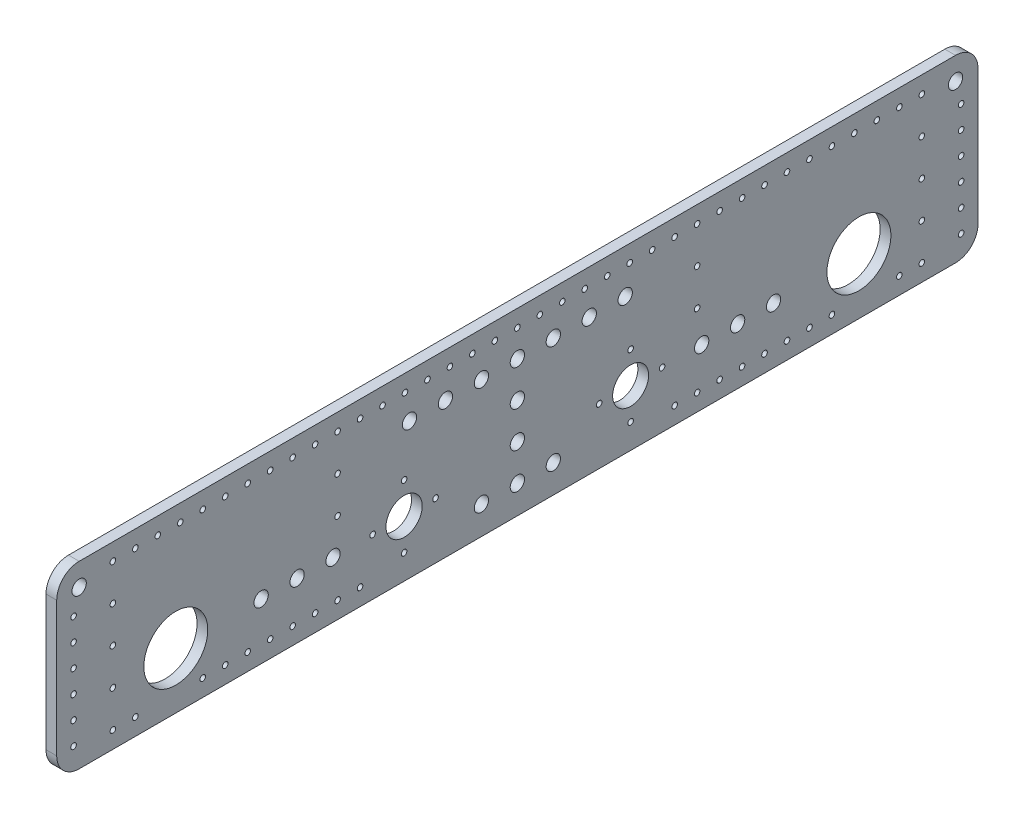
SolidWorks part; units mm, degrees
ref_plane "Front Plane" through (0, 0, 0) normal (0, 0, 1) x (1, 0, 0)
ref_plane "Top Plane" through (0, 0, 0) normal (0, 1, 0) x (1, 0, 0)
ref_plane "Right Plane" through (0, 0, 0) normal (1, 0, 0) x (0, 0, -1)
sketch "Sketch2" plane through (0, 0, 0) normal (1, 0, 0) x (0, 0, -1)
  line L0 (-23.4723, 28.6683) -> (-23.4723, -31.3317)
  line L1 (-13.4723, 38.6683) -> (376.5277, 38.6683)
  line L2 (-13.4723, -41.3317) -> (376.5277, -41.3317)
  line L3 (386.5277, 28.6683) -> (386.5277, -31.3317)
  circle A1 centre (29.5277, -16.3317) radius 14.225
  circle A2 centre (333.5277, -16.3317) radius 14.225
  arc A15 (-23.4723, 28.6683) -> (-13.4723, 38.6683) centre (-13.4723, 28.6683) cw
  arc A16 (-13.4723, -41.3317) -> (-23.4723, -31.3317) centre (-13.4723, -31.3317) cw
  arc A17 (386.5277, 28.6683) -> (376.5277, 38.6683) centre (376.5277, 28.6683) ccw
  arc A18 (376.5277, -41.3317) -> (386.5277, -31.3317) centre (376.5277, -31.3317) ccw
  circle A59 centre (181.5277, -28.7717) radius 3.18
  circle A60 centre (197.5277, -28.7717) radius 3.18
  circle A63 centre (197.5277, 19.2283) radius 3.18
  circle A64 centre (181.5277, -12.7717) radius 3.18
  circle A65 centre (181.5277, 3.2283) radius 3.18
  circle A66 centre (181.5277, 19.2283) radius 3.18
  circle A67 centre (165.5277, -28.7717) radius 3.18
  circle A68 centre (165.5277, 19.2283) radius 3.18
  circle A69 centre (197.5277, -12.7717) radius 3.18 [skipped]
  circle A70 centre (197.5277, 3.2283) radius 3.18 [skipped]
  circle A71 centre (-8.4723, 31.1683) radius 1.25 construction
  circle A150 centre (83.5027, -16.3317) radius 3.18
  circle A151 centre (279.5527, -16.3317) radius 3.18
  circle A152 centre (1.5277, 31.1683) radius 1.25
  circle A153 centre (11.5277, 31.1683) radius 1.25
  circle A154 centre (21.5277, 31.1683) radius 1.25
  circle A155 centre (31.5277, 31.1683) radius 1.25
  circle A156 centre (41.5277, 31.1683) radius 1.25
  circle A157 centre (51.5277, 31.1683) radius 1.25
  circle A158 centre (61.5277, 31.1683) radius 1.25
  circle A159 centre (71.5277, 31.1683) radius 1.25
  circle A160 centre (81.5277, 31.1683) radius 1.25
  circle A161 centre (91.5277, 31.1683) radius 1.25
  circle A162 centre (101.5277, 31.1683) radius 1.25
  circle A163 centre (111.5277, 31.1683) radius 1.25
  circle A164 centre (121.5277, 31.1683) radius 1.25
  circle A165 centre (131.5277, 31.1683) radius 1.25
  circle A166 centre (141.5277, 31.1683) radius 1.25
  circle A167 centre (151.5277, 31.1683) radius 1.25
  circle A168 centre (161.5277, 31.1683) radius 1.25
  circle A169 centre (171.5277, 31.1683) radius 1.25
  circle A170 centre (181.5277, 31.1683) radius 1.25
  circle A171 centre (191.5277, 31.1683) radius 1.25
  circle A172 centre (201.5277, 31.1683) radius 1.25
  circle A173 centre (211.5277, 31.1683) radius 1.25
  circle A174 centre (221.5277, 31.1683) radius 1.25
  circle A175 centre (231.5277, 31.1683) radius 1.25
  circle A176 centre (241.5277, 31.1683) radius 1.25
  circle A177 centre (251.5277, 31.1683) radius 1.25
  circle A178 centre (261.5277, 31.1683) radius 1.25
  circle A179 centre (271.5277, 31.1683) radius 1.25
  circle A180 centre (281.5277, 31.1683) radius 1.25
  circle A181 centre (291.5277, 31.1683) radius 1.25
  circle A182 centre (301.5277, 31.1683) radius 1.25
  circle A183 centre (311.5277, 31.1683) radius 1.25
  circle A184 centre (321.5277, 31.1683) radius 1.25
  circle A185 centre (331.5277, 31.1683) radius 1.25
  circle A186 centre (341.5277, 31.1683) radius 1.25
  circle A187 centre (351.5277, 31.1683) radius 1.25
  circle A188 centre (361.5277, 31.1683) radius 1.25
  circle A190 centre (1.5277, -33.8317) radius 1.25
  circle A191 centre (11.5277, -33.8317) radius 1.25
  circle A194 centre (41.5277, -33.8317) radius 1.25
  circle A195 centre (51.5277, -33.8317) radius 1.25
  circle A196 centre (61.5277, -33.8317) radius 1.25
  circle A197 centre (71.5277, -33.8317) radius 1.25
  circle A198 centre (81.5277, -33.8317) radius 1.25
  circle A199 centre (91.5277, -33.8317) radius 1.25
  circle A200 centre (101.5277, -33.8317) radius 1.25
  circle A201 centre (111.5277, -33.8317) radius 1.25
  circle A215 centre (251.5277, -33.8317) radius 1.25
  circle A216 centre (261.5277, -33.8317) radius 1.25
  circle A217 centre (271.5277, -33.8317) radius 1.25
  circle A218 centre (281.5277, -33.8317) radius 1.25
  circle A219 centre (291.5277, -33.8317) radius 1.25
  circle A220 centre (301.5277, -33.8317) radius 1.25
  circle A221 centre (311.5277, -33.8317) radius 1.25
  circle A222 centre (321.5277, -33.8317) radius 1.25
  circle A225 centre (351.5277, -33.8317) radius 1.25
  circle A226 centre (361.5277, -33.8317) radius 1.25
  circle A229 centre (181.5277, -33.8317) radius 1.25 [skipped]
  circle A230 centre (201.5277, -33.8317) radius 1.25 [skipped]
  circle A231 centre (161.5277, -33.8317) radius 1.25 [skipped]
  circle A232 centre (151.5277, -33.8317) radius 1.25 [skipped]
  circle A233 centre (141.5277, -33.8317) radius 1.25 [skipped]
  circle A234 centre (131.5277, -33.8317) radius 1.25 [skipped]
  circle A235 centre (171.5277, -33.8317) radius 1.25 [skipped]
  circle A236 centre (191.5277, -33.8317) radius 1.25 [skipped]
  circle A237 centre (211.5277, -33.8317) radius 1.25 [skipped]
  circle A238 centre (221.5277, -33.8317) radius 1.25 [skipped]
  circle A239 centre (231.5277, -33.8317) radius 1.25 [skipped]
  circle A240 centre (31.5277, -33.8317) radius 1.25 [skipped]
  circle A241 centre (21.5277, -33.8317) radius 1.25 [skipped]
  circle A242 centre (331.5277, -33.8317) radius 1.25 [skipped]
  circle A243 centre (341.5277, -33.8317) radius 1.25 [skipped]
  circle A245 centre (-13.4723, 28.6683) radius 3.18
  circle A247 centre (376.5277, 28.6683) radius 3.18
  circle A248 centre (371.5277, 31.1683) radius 1.25 [skipped]
  circle A249 centre (371.5277, -33.8317) radius 1.25 [skipped]
  circle A250 centre (-8.4723, -33.8317) radius 1.25 [skipped]
  circle A254 centre (295.5527, -16.3317) radius 3.18
  circle A255 centre (67.5027, -16.3317) radius 3.18
  circle A256 centre (263.5527, -16.3317) radius 3.18
  circle A257 centre (121.5277, -33.8317) radius 1.25 [skipped]
  circle A260 centre (131.1277, -30.3317) radius 1.25
  circle A261 centre (145.1277, -16.3317) radius 1.25
  circle A262 centre (131.1277, -2.3317) radius 1.25
  circle A263 centre (117.1277, -16.3317) radius 1.25
  circle A264 centre (231.9277, -30.3317) radius 1.25
  circle A265 centre (217.9277, -16.3317) radius 1.25
  circle A266 centre (231.9277, -2.3317) radius 1.25
  circle A267 centre (245.9277, -16.3317) radius 1.25
  circle A268 centre (231.9277, -16.3317) radius 8
  circle A269 centre (131.1277, -16.3317) radius 8.0683
  circle A270 centre (241.5277, -33.8317) radius 1.25 [skipped]
  circle A271 centre (-15.9723, 18.6683) radius 1.25
  circle A272 centre (379.0277, 18.6683) radius 1.25
  circle A273 centre (379.0277, 8.6683) radius 1.25
  circle A274 centre (379.0277, -1.3317) radius 1.25
  circle A275 centre (379.0277, -11.3317) radius 1.25
  circle A276 centre (379.0277, -21.3317) radius 1.25
  circle A277 centre (379.0277, -31.3317) radius 1.25
  circle A278 centre (-15.9723, 8.6683) radius 1.25
  circle A279 centre (-15.9723, -1.3317) radius 1.25
  circle A280 centre (-15.9723, -11.3317) radius 1.25
  circle A281 centre (-15.9723, -21.3317) radius 1.25
  circle A282 centre (-15.9723, -31.3317) radius 1.25
  circle A284 centre (101.5277, -1.3317) radius 1.25
  circle A285 centre (101.5277, 14.9183) radius 1.25
  arc A286 (101.4697, -18.8304) -> (102.6179, -16.9702) centre (99.5027, -16.3317) ccw [skipped]
  circle A287 centre (361.5277, -17.5817) radius 1.25
  circle A288 centre (361.5277, -1.3317) radius 1.25
  circle A289 centre (361.5277, 14.9183) radius 1.25
  circle A290 centre (1.5277, -17.5817) radius 1.25
  circle A291 centre (1.5277, -1.3317) radius 1.25
  circle A292 centre (1.5277, 14.9183) radius 1.25
  circle A293 centre (101.5277, -17.5817) radius 1.25 [skipped]
  circle A294 centre (99.5027, -16.3317) radius 3.18
  circle A298 centre (261.5277, -1.3317) radius 1.25
  circle A300 centre (261.5277, 14.9183) radius 1.25
  arc A301 (260.4374, -16.9702) -> (261.5857, -18.8304) centre (261.5277, -17.5817) ccw [skipped]
  arc A302 (80.4021, 31.712) -> (81.5373, 29.9183) centre (83.5027, 32.4183) ccw [skipped]
  circle A303 centre (83.5027, 16.1683) radius 3.18 [skipped]
  circle A304 centre (83.5027, -0.0817) radius 3.18 [skipped]
  circle A305 centre (149.5277, 19.2283) radius 3.18
  circle A306 centre (133.5277, 19.2283) radius 3.18
  circle A307 centre (213.5277, 19.2283) radius 3.18
  circle A308 centre (229.5277, 19.2283) radius 3.18
  point P32 (-23.4723, 38.6683)
  point P35 (-23.4723, -41.3317)
  point P40 (386.5277, -41.3317)
  point P123 (181.5277, -41.3317)
  dimension "D3" = 25
  dimension "D7" = 10
  dimension "D8" = 10
  dimension "D9" = 10
  dimension "D10" = 10
  dimension "D11" = 7.5
  dimension "D13" = 12.56
  dimension "D20" = 7.5
  dimension "D35" = 60.56
  dimension "D36" = 11
  dimension "D37" = 25
  dimension "D38" = 39
  dimension "D39" = 357
  dimension "D40" = 10
  dimension "D41" = 275
  dimension "D42" = 28.45
  dimension "D43" = 16.1366
  dimension "D44" = 7.5
  dimension "D55" = 173
  dimension "D56" = 189
  dimension "D57" = 205
  dimension "D58" = 221
  dimension "D59" = 237
  dimension "D60" = 253
  dimension "D61" = 255.4
  dimension "D62" = 269.4
  dimension "D66" = 90.975
  dimension "D67" = 106.975
  dimension "D68" = 122.975
  dimension "D69" = 287.025
  dimension "D70" = 303.025
  dimension "D71" = 319.025
  dimension "D72" = 400
  dimension "D73" = 402.5
  dimension "D1" = 80
  dimension "D2" = 410
  dimension "D4" = 53
  dimension "D5" = 25
  dimension "D12" = 15
  dimension "D14" = 205
  dimension "D21" = 20
  dimension "D31" = 3
  dimension "D32" = 28.56
  dimension "D33" = 44.56
  dimension "D34" = 3
  dimension "D45" = 10
  dimension "D46" = 20
  dimension "D47" = 25
  dimension "D48" = 10
  dimension "D49" = 7.5
  dimension "D50" = 23.75
  dimension "D51" = 40
  dimension "D52" = 56.25
  dimension "D53" = 72.5
  dimension "D54" = 157
  dimension "D63" = 241.4
  dimension "D64" = 65
  dimension "D65" = 25
  dimension "D15" = 2
  dimension "D16" = 4
  dimension "D17" = 2
  dimension "D18" = 39
  dimension "D19" = 2
  dimension "D22" = 2
  dimension "D23" = 2
  dimension "D24" = 2
  dimension "D25" = 6
  dimension "D26" = 4
  dimension "D27" = 4
  dimension "D28" = 4
  dimension "D29" = 2
  dimension "D30" = 4
extrude "Boss-Extrude1" add sketch "Sketch2" along normal blind 4.7625
